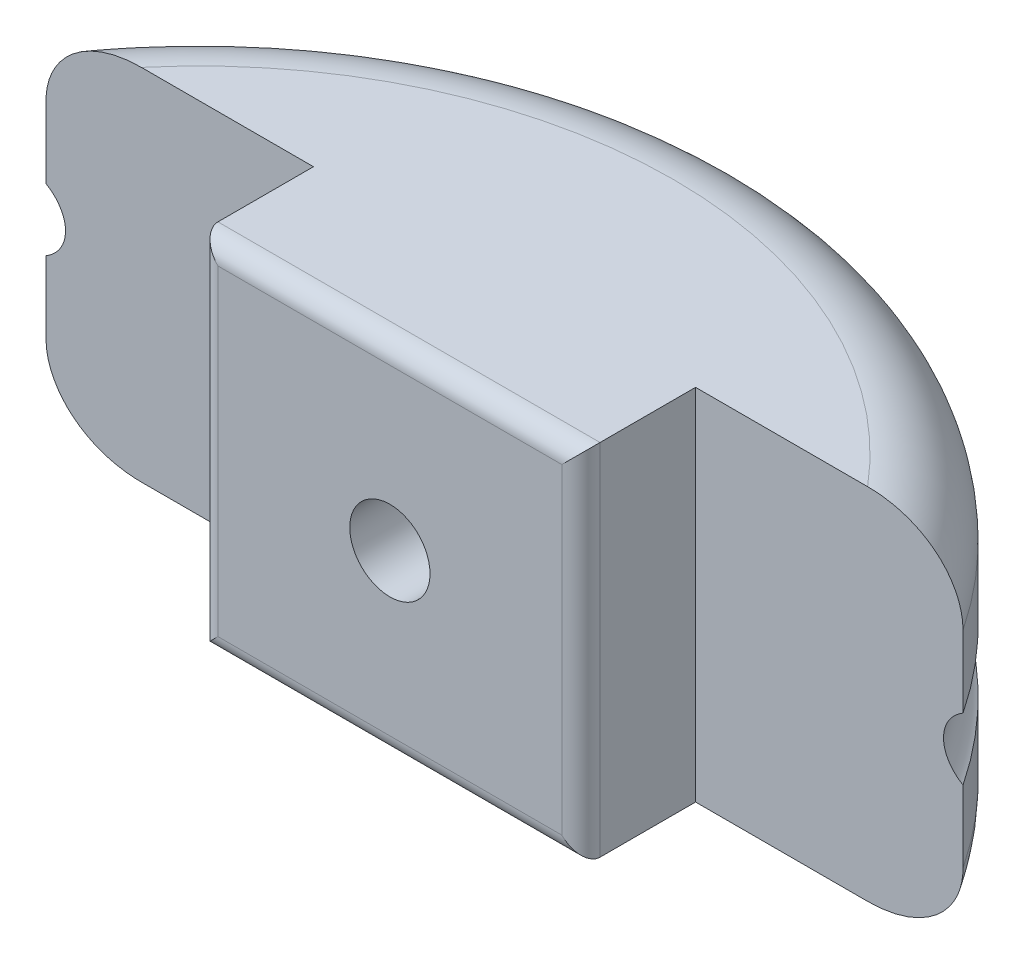
SolidWorks part; units mm, degrees
ref_plane "Plan de face" through (0, 0, 0) normal (0, 0, 1) x (1, 0, 0)
ref_plane "Plan de dessus" through (0, 0, 0) normal (0, 1, 0) x (1, 0, 0)
ref_plane "Plan de droite" through (0, 0, 0) normal (1, 0, 0) x (0, 0, -1)
sketch "Esquisse1" plane through (0, 0, 0) normal (0, 1, 0) x (1, 0, 0)
  line L0 (0, 0) -> (10, 0)
  line L1 (10, 0) -> (10, 3)
  line L2 (10, 3) -> (17, 3)
  line L3 (0, 0) -> (0, 3)
  line L4 (0, 3) -> (-7, 3)
  line L5 (5, 0) -> (5, 10) construction
  line L6 (5, 0) -> (5, -5) construction
  arc A0 (-7, 3) -> (17, 3) centre (5, -5) cw
extrude "Boss.-Extru.2" add sketch "Esquisse1" along normal blind 9.4 contours A0 L4 L3 L0 L1 L2
ref_plane "Plan1" through (0, 0, 5) normal (0, 0, 1) x (1, 0, 0)
sketch "Esquisse13" plane through (0, 0, 5) normal (0, 0, 1) x (1, 0, 0)
  line L0 (5, 9.4) -> (5, 0) construction
  line L1 (0, 9.4) -> (10, 9.4) construction
  line L2 (0, 0) -> (10, 0) construction
  line L3 (5, 4.7) -> (-10, 4.7) construction
  circle A4 centre (-10, 4.7) radius 1
revolve "Enlèvement de matière-Révolution4" cut sketch "Esquisse13" angle 360 about L0
sketch "Esquisse14" plane through (0, 0, 0) normal (0, 0, 1) x (1, 0, 0)
  line L0 (0, 4.7) -> (5, 4.7) construction
  line L1 (0, 9.4) -> (0, 0) construction
  circle A0 centre (5, 4.7) radius 1.05
extrude "Enlèv. mat.-Extru.1" cut sketch "Esquisse14" against normal through all
ref_plane "Plan2" through (0, 0, -10) normal (0, 0, 1) x (1, 0, 0)
sketch "Esquisse15" plane through (0, 0, -10) normal (0, 0, 1) x (1, 0, 0)
  circle A0 centre (5, 4.7) radius 2.5
extrude "Enlèv. mat.-Extru.2" cut sketch "Esquisse15" along normal blind 8.4
fillet "Congé2" radius 0.5 4 edges at (5, 9.4, 0) (0, 4.7, 0) (10, 4.7, 0) (5, 0, 0)
fillet "Congé3" radius 2 2 edges at (5, 9.4, -9.4222) (5, 0, -9.4222)
